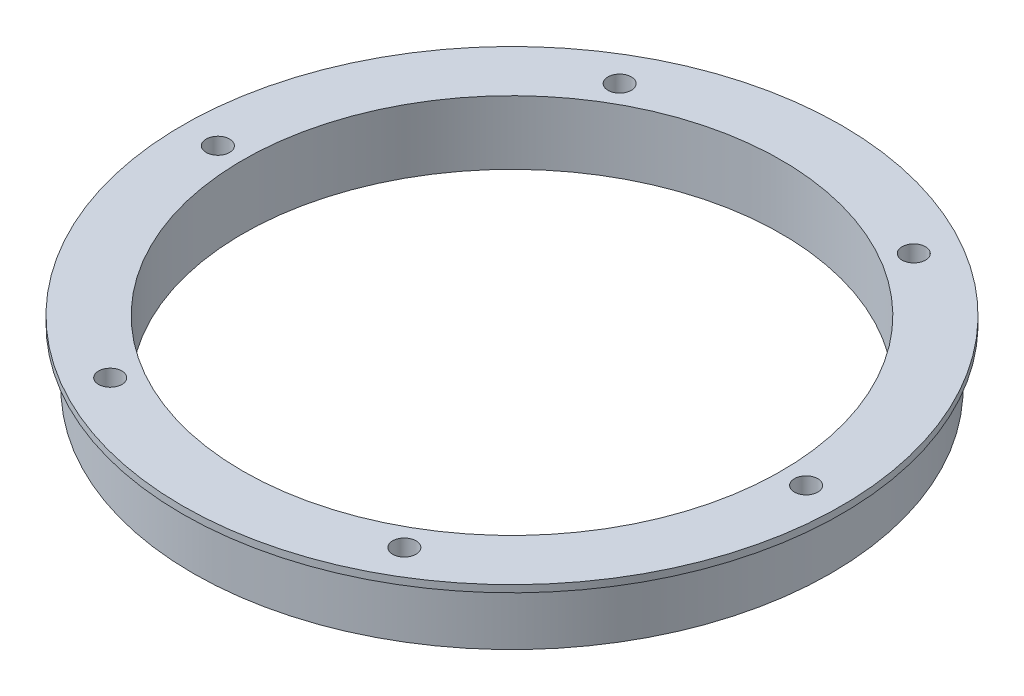
SolidWorks part; units mm, degrees
material "6061 合金"
ref_plane "前视基准面" through (0, 0, 0) normal (0, 0, 1) x (1, 0, 0)
ref_plane "上视基准面" through (0, 0, 0) normal (0, 1, 0) x (1, 0, 0)
ref_plane "右视基准面" through (0, 0, 0) normal (1, 0, 0) x (0, 0, -1)
sketch "草图2" plane through (0, 0, 0) normal (0, 1, 0) x (1, 0, 0)
  circle A0 centre (0, 0) radius 45
  circle A1 centre (0, 0) radius 38
  dimension "D1" = 7
  dimension "D2" = 90
extrude "凸台-拉伸1" add sketch "草图2" along normal blind 8
sketch "草图6" plane through (0, 8, 0) normal (0, 1, 0) x (1, 0, 0)
  circle A0 centre (0, 0) radius 38 construction
  circle A1 centre (0, 0) radius 38
  circle A2 centre (0, 0) radius 46.5
  circle A3 centre (0, 0) radius 45 construction
  dimension "D1" = 1.5
extrude "凸台-拉伸3" add sketch "草图6" along normal blind 1
hole_wizard "M4 螺纹孔1" positions "草图4" profile "草图5" tap size "M4" standard "GB" end condition through all
sketch "草图4" plane through (0, 9, 0) normal (0, 1, 0) x (1, 0, 0)
  circle A0 centre (0, 0) radius 41.5 construction
  circle A2 centre (0, 0) radius 38 construction
  point P0 (-20.75, 35.9401)
  point P29 (20.75, 35.9401)
  point P30 (41.5, 0)
  point P31 (20.75, -35.9401)
  point P32 (-20.75, -35.9401)
  point P33 (-41.5, 0)
  point P35 (13.367, 39.2883)
  point P36 (40.2329, 10.1767)
  point P37 (-20.9366, 35.8317)
  dimension "D1" = 3.5
  dimension "D2" = 6
sketch "草图5" plane through (-20.75, 9, -35.9401) normal (1, 0, 0) x (0, 0, 1)
  line L0 (0, 0) -> (0, 9)
  line L1 (0, 9) -> (1.65, 9)
  line L2 (1.65, 9) -> (1.65, 0)
  line L5 (1.65, 0) -> (0, 0)
  line L11 (0, -6.35) -> (0, 107.95) construction
  dimension "通孔螺纹孔钻头直径" = 3.3
  dimension "通孔螺纹孔钻头深度" = 9
cosmetic thread "孔螺蚊线5"
cosmetic thread "孔螺蚊线6"
cosmetic thread "孔螺蚊线7"
cosmetic thread "孔螺蚊线8"
cosmetic thread "孔螺蚊线9"
cosmetic thread "孔螺蚊线10"
